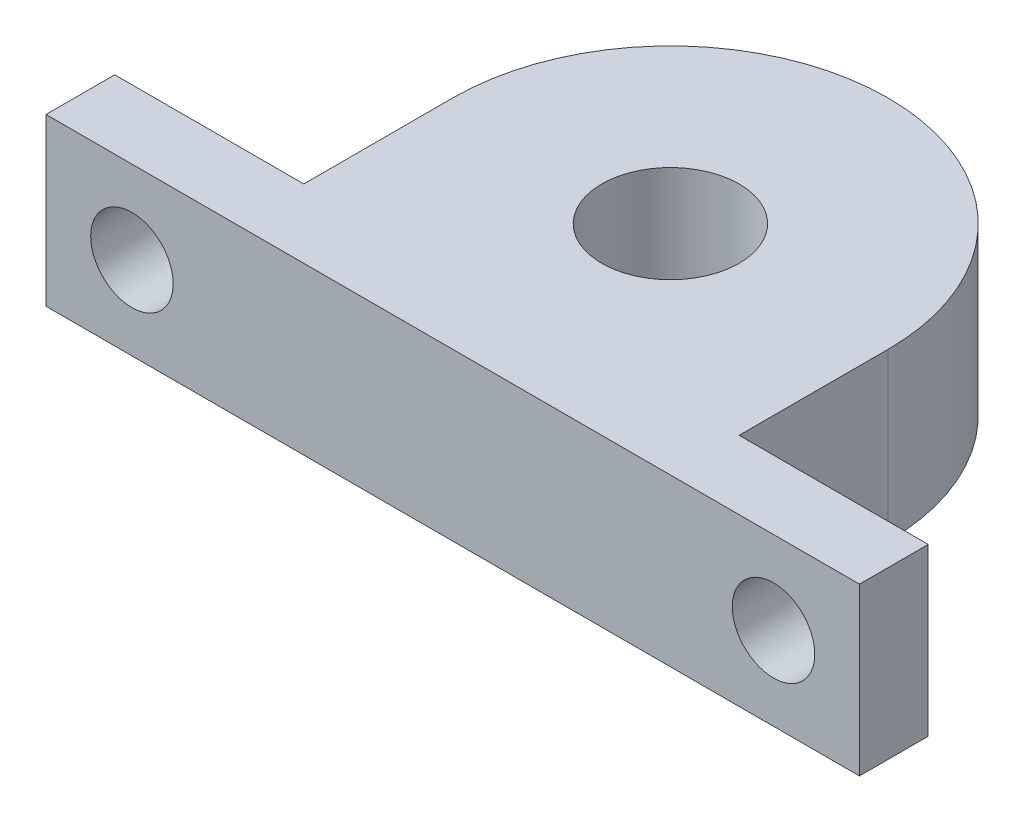
SolidWorks part; units mm, degrees
ref_plane "前视基准面" through (0, 0, 0) normal (0, 0, 1) x (1, 0, 0)
ref_plane "上视基准面" through (0, 0, 0) normal (0, 1, 0) x (1, 0, 0)
ref_plane "右视基准面" through (0, 0, 0) normal (1, 0, 0) x (0, 0, -1)
other "Configuration Table"
sketch "草图1" plane through (0, 0, 0) normal (0, 1, 0) x (1, 0, 0)
  line L0 (35.5, -19) -> (-35.5, -19)
  line L1 (-35.5, -19) -> (-35.5, -13)
  line L2 (-35.5, -13) -> (-13.8564, -13)
  line L3 (-19, 0) -> (-19, -13)
  line L4 (0, -1000) -> (0, 49000) construction
  line L5 (35.5, -19) -> (35.5, -13)
  line L6 (19, 0) -> (19, -13)
  line L7 (35.5, -13) -> (13.8564, -13)
  circle A0 centre (0, 0) radius 6
  circle A1 centre (0, 0) radius 19
  point P13 (0, -19)
  dimension "D1" = 12
  dimension "D2" = 38
  dimension "D3" = 35.5
  dimension "D4" = 6
extrude "凸台-拉伸2" add sketch "草图1" along normal blind 14.5 contours A1 L4 A0 | L4 A1 A0 | A1 L3 L2 | A1 L7 L6 | A1 L0 L5 L7 | A1 L2 L1 L0
sketch "草图2" plane through (0, 0, 13) normal (0, 0, -1) x (-1, 0, 0)
  line L0 (-1035.5, 7.25) -> (48964.5, 7.25) construction
  line L1 (-35.5, 14.5) -> (-35.5, 0) construction
  line L2 (0, -1000) -> (0, 49000) construction
  circle A0 centre (-28, 7.25) radius 3.6
  circle A1 centre (28, 7.25) radius 3.6
  point P5 (-35.5, 7.25)
  dimension "D1" = 7.2
  dimension "D2" = 28
extrude "切除-拉伸1" cut sketch "草图2" against normal blind 14.5
